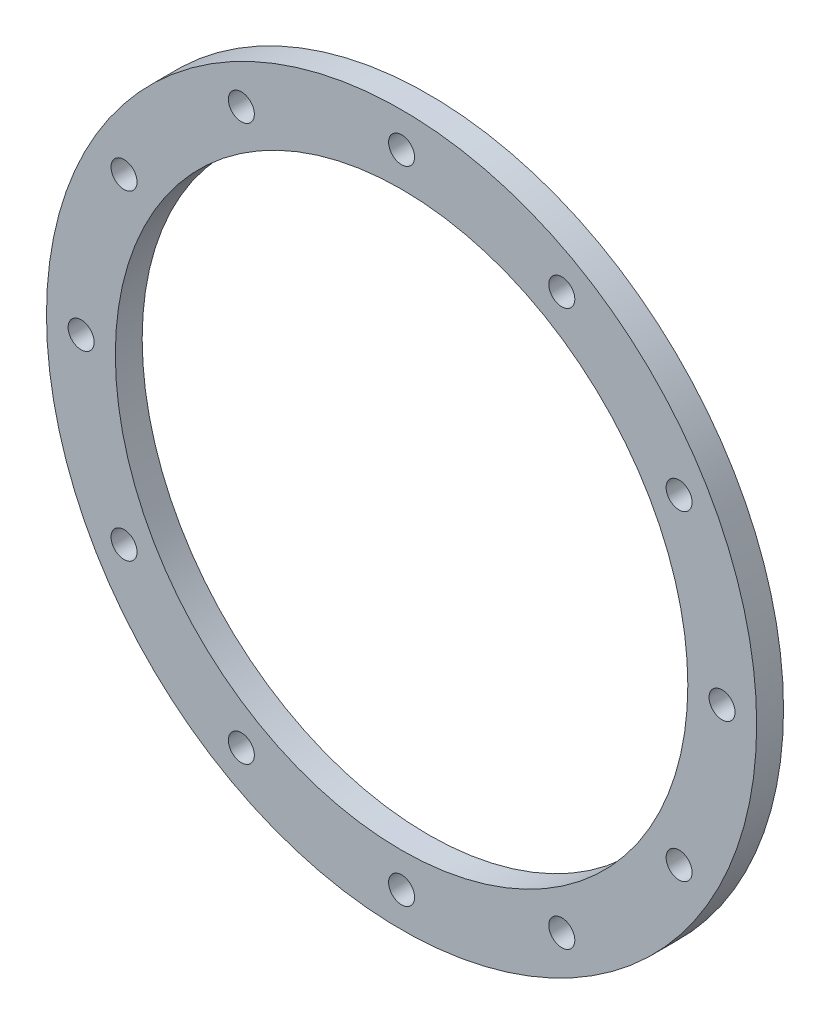
SolidWorks part; units mm, degrees
material "轻木"
ref_plane "前视基准面" through (0, 0, 0) normal (0, 0, 1) x (1, 0, 0)
ref_plane "上视基准面" through (0, 0, 0) normal (0, 1, 0) x (1, 0, 0)
ref_plane "右视基准面" through (0, 0, 0) normal (1, 0, 0) x (0, 0, -1)
sketch "草图1" plane through (0, 0, 0) normal (0, 0, 1) x (1, 0, 0)
  circle A0 centre (0, 0) radius 33.05
  circle A1 centre (0, 0) radius 37 construction
  circle A2 centre (0, 0) radius 41
  circle A3 centre (0, 37) radius 1.5
  circle A4 centre (18.5, 32.0429) radius 1.5
  circle A5 centre (32.0429, 18.5) radius 1.5
  circle A6 centre (37, 0) radius 1.5
  circle A7 centre (32.0429, -18.5) radius 1.5
  circle A8 centre (18.5, -32.0429) radius 1.5
  circle A9 centre (0, -37) radius 1.5
  circle A10 centre (-18.5, -32.0429) radius 1.5
  circle A11 centre (-32.0429, -18.5) radius 1.5
  circle A12 centre (-37, 0) radius 1.5
  circle A13 centre (-32.0429, 18.5) radius 1.5
  circle A14 centre (-18.5, 32.0429) radius 1.5
  dimension "D1" = 74
  dimension "D2" = 66.1
  dimension "D4" = 3
  dimension "D3" = 4
  dimension "D5" = 12
extrude "凸台-拉伸1" add sketch "草图1" along normal blind 3.1
